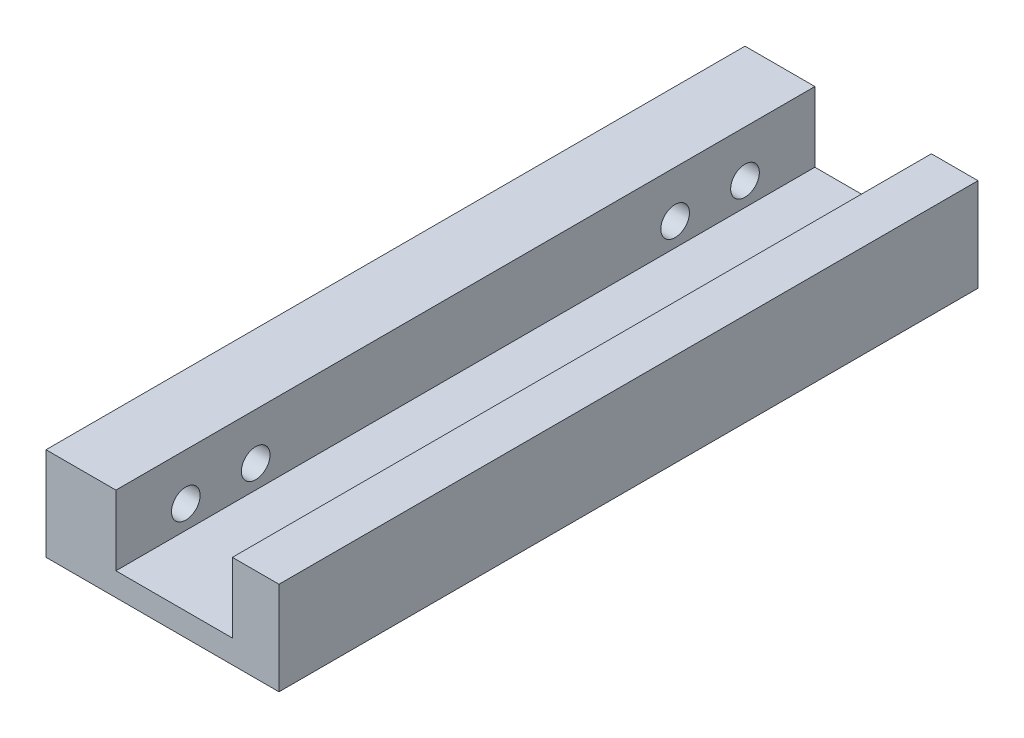
SolidWorks part; units mm, degrees
ref_plane "Front Plane" through (0, 0, 0) normal (0, 0, 1) x (1, 0, 0)
ref_plane "Top Plane" through (0, 0, 0) normal (0, 1, 0) x (1, 0, 0)
ref_plane "Right Plane" through (0, 0, 0) normal (1, 0, 0) x (0, 0, -1)
sketch "Sketch1" plane through (0, 0, 0) normal (0, 0, 1) x (1, 0, 0)
  line L0 (0, 0) -> (3, 0)
  line L1 (3, 0) -> (3, -3)
  line L2 (3, -3) -> (8, -3)
  line L3 (8, -3) -> (8, 0)
  line L4 (8, 0) -> (10, 0)
  line L5 (10, 0) -> (10, -4)
  line L6 (10, -4) -> (0, -4)
  line L7 (0, -4) -> (0, 0)
  dimension "D1" = 2
  dimension "D2" = 3
  dimension "D3" = 4
  dimension "D4" = 1
  dimension "D5" = 10
extrude "Boss-Extrude1" add sketch "Sketch1" along normal blind 30
sketch "Sketch2" plane through (0, 0, 0) normal (-1, 0, 0) x (0, 0, 1)
  line L0 (0, -2) -> (3, -2) construction
  line L1 (0, 0) -> (0, -4) construction
  line L2 (3, -2) -> (6, -2) construction
  line L3 (30, -2) -> (27, -2) construction
  line L4 (30, 0) -> (30, -4) construction
  line L5 (27, -2) -> (24, -2) construction
  circle A0 centre (3, -2) radius 0.615
  circle A1 centre (6, -2) radius 0.615
  circle A2 centre (24, -2) radius 0.615
  circle A3 centre (27, -2) radius 0.615
  dimension "D1" = 1.23
  dimension "D2" = 3
  dimension "D3" = 3
extrude "Cut-Extrude1" cut sketch "Sketch2" against normal up to surface (3 mm away) up to face at (3, -1.5, 15)
